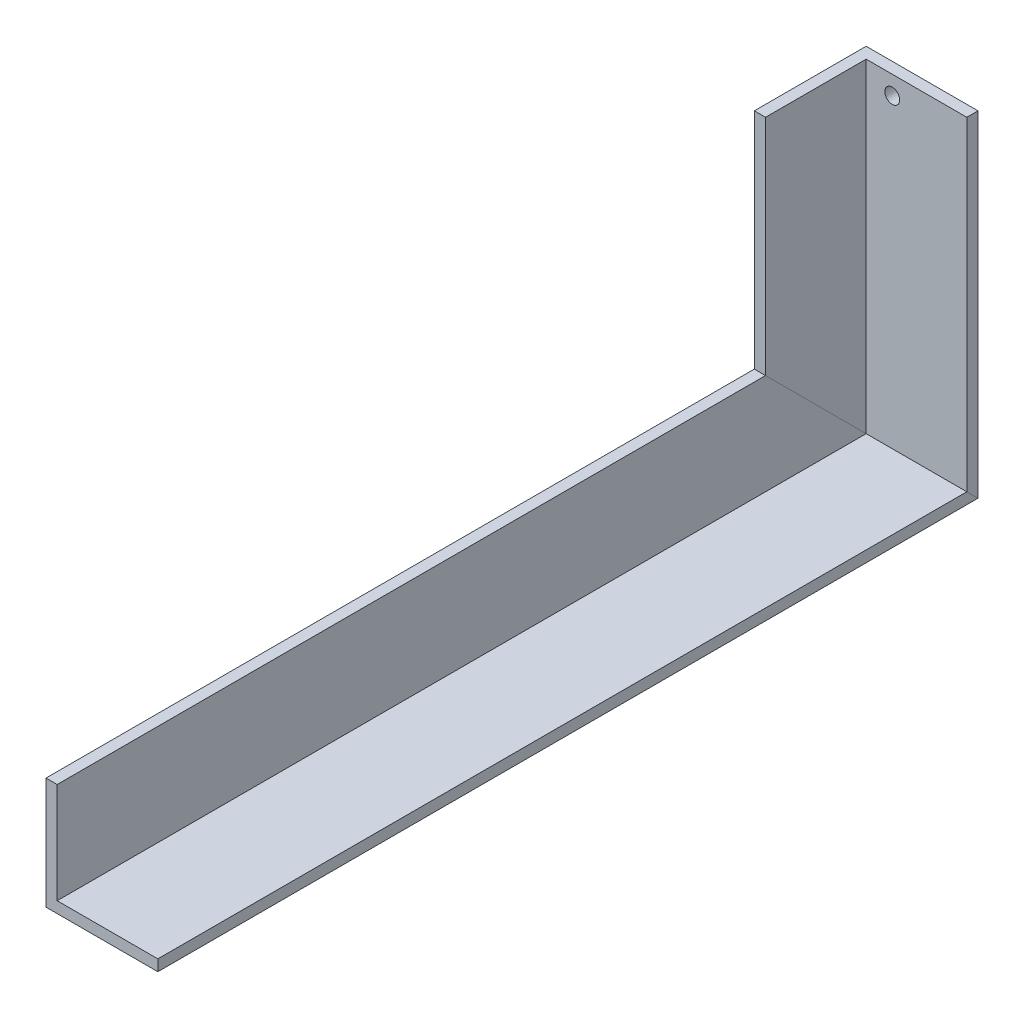
SolidWorks part; units mm, degrees
ref_plane "Front Plane" through (0, 0, 0) normal (0, 0, 1) x (1, 0, 0)
ref_plane "Top Plane" through (0, 0, 0) normal (0, 1, 0) x (1, 0, 0)
ref_plane "Right Plane" through (0, 0, 0) normal (1, 0, 0) x (0, 0, -1)
sketch "Sketch2" plane through (0, 0, 0) normal (0, 0, 1) x (1, 0, 0)
  line L0 (0, 0) -> (30, 0)
  line L1 (30, 0) -> (30, 3)
  line L2 (30, 3) -> (3, 3)
  line L3 (3, 3) -> (3, 30)
  line L4 (3, 30) -> (0, 30)
  line L5 (0, 30) -> (0, 0)
  dimension "D1" = 30
  dimension "D2" = 3
  dimension "D3" = 30
  dimension "D4" = 3
sketch "Sketch4" plane through (0, 0, 0) normal (1, 0, 0) x (0, 0, -1)
  line L0 (0, 0) -> (220, 0)
  line L1 (220, 0) -> (220, 90)
  dimension "D1" = 220
  dimension "D2" = 90
sweep "Sweep1" add profiles "Sketch2" path "Sketch4"
sketch "Sketch13" plane through (0, 0, -220) normal (0, 0, -1) x (-1, 0, 0)
  circle A0 centre (-10, 85) radius 2 construction
  circle A1 centre (-10, 85) radius 2
extrude "Cut-Extrude1" cut sketch "Sketch13" against normal blind 10
